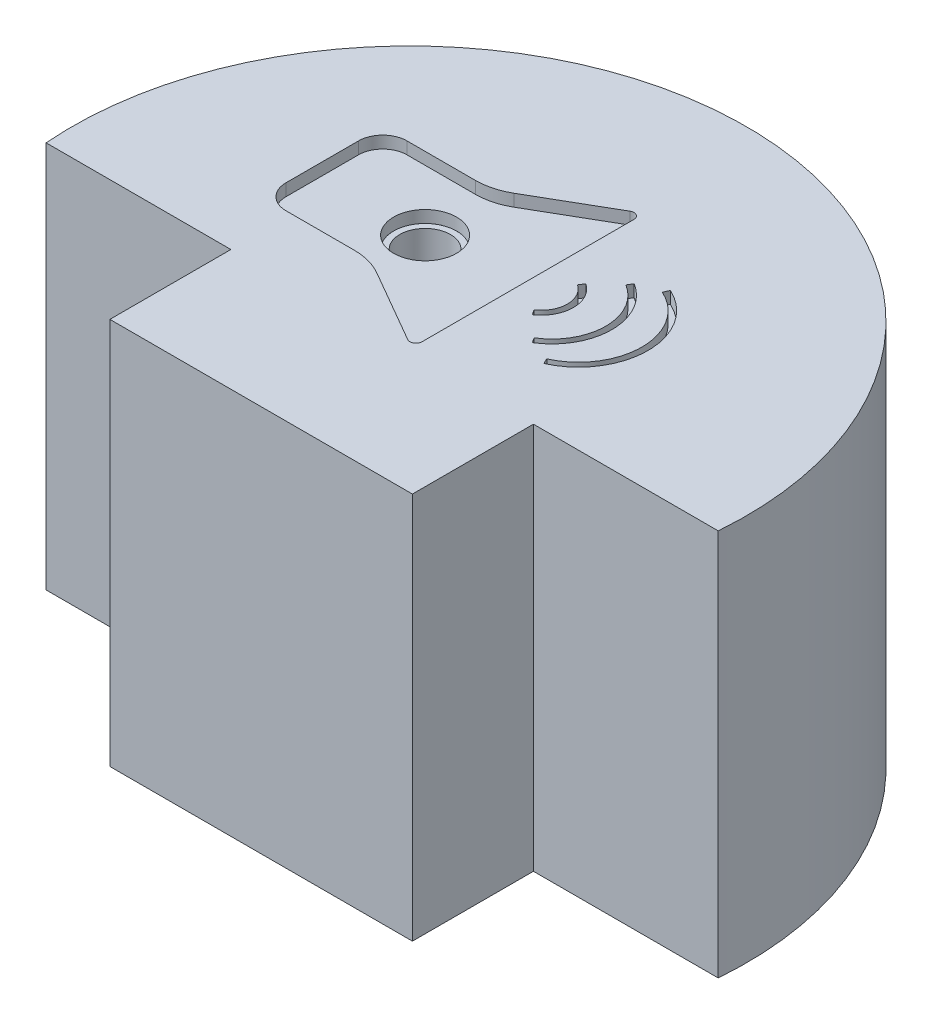
SolidWorks part; units mm, degrees
ref_plane "Alzado" through (0, 0, 0) normal (0, 0, 1) x (1, 0, 0)
ref_plane "Planta" through (0, 0, 0) normal (0, 1, 0) x (1, 0, 0)
ref_plane "Vista lateral" through (0, 0, 0) normal (1, 0, 0) x (0, 0, -1)
sketch "Croquis1" plane through (0, 0, 0) normal (0, 1, 0) x (1, 0, 0)
  line L0 (0, 0) -> (0, 40.0976) construction
  line L1 (-12.5, 0) -> (12.5, 0)
  line L2 (-12.5, 0) -> (-12.5, 10)
  line L3 (12.5, 0) -> (12.5, 10)
  line L4 (-12.5, 10) -> (-27.77, 10)
  line L5 (12.5, 10) -> (27.77, 10)
  arc A0 (-27.77, 10) -> (27.77, 10) centre (0, 12.2376) cw
  point P10 (0, 40.0976)
  dimension "D4" = 27.86
  dimension "D1" = 25
  dimension "D2" = 10
  dimension "D3" = 15.27
extrude "Extruir-Lámina1" add sketch "Croquis1" along normal blind 30 thin thin type one direction reverse wall 2
sketch "Croquis2" plane through (0, 30, 0) normal (0, 1, 0) x (1, 0, 0)
  line L0 (12.5, 10) -> (27.77, 10) construction
  line L1 (12.5, 0) -> (12.5, 10) construction
  line L2 (-12.5, 0) -> (12.5, 0) construction
  line L3 (-12.5, 10) -> (-12.5, 0) construction
  line L4 (-27.77, 10) -> (-12.5, 10) construction
  line L5 (12.5, 10) -> (27.77, 10)
  line L6 (12.5, 0) -> (12.5, 10)
  line L7 (-12.5, 0) -> (12.5, 0)
  line L8 (-12.5, 10) -> (-12.5, 0)
  line L9 (-27.77, 10) -> (-12.5, 10)
  arc A0 (27.77, 10) -> (-27.77, 10) centre (0, 12.2376) ccw construction
  arc A1 (27.77, 10) -> (-27.77, 10) centre (0, 12.2376) ccw
extrude "Saliente-Extruir1" add sketch "Croquis2" along normal blind 2
sketch "Croquis3" plane through (0, 32, 0) normal (0, 1, 0) x (1, 0, 0)
  line L0 (0, 0) -> (0, 40.0976) construction
  line L1 (-14.7383, 20.0488) -> (14.7383, 20.0488) construction
  line L2 (-15, 23.0488) -> (-15, 17.0488)
  line L3 (-13, 25.0488) -> (-7.3397, 25.0488)
  line L4 (-4.8397, 25.7187) -> (1.25, 29.2346)
  line L5 (-4.8397, 14.3789) -> (1.25, 10.863)
  line L6 (-13, 15.0488) -> (-7.3397, 15.0488)
  line L7 (2, 28.8016) -> (2, 11.296)
  arc A0 (27.77, 10) -> (-27.77, 10) centre (0, 12.2376) ccw construction
  arc A1 (-15, 17.0488) -> (-13, 15.0488) centre (-13, 17.0488) ccw
  arc A2 (-15, 23.0488) -> (-13, 25.0488) centre (-13, 23.0488) cw
  arc A3 (-4.8397, 14.3789) -> (-7.3397, 15.0488) centre (-7.3397, 10.0488) ccw
  arc A4 (-7.3397, 25.0488) -> (-4.8397, 25.7187) centre (-7.3397, 30.0488) ccw
  arc A5 (1.25, 10.863) -> (2, 11.296) centre (1.5, 11.296) ccw
  arc A6 (1.25, 29.2346) -> (2, 28.8016) centre (1.5, 28.8016) cw
  point P8 (0, 20.0488)
  point P17 (-15, 15.0488)
  point P20 (-15, 25.0488)
  point P23 (-6, 15.0488)
  point P26 (-6, 25.0488)
  point P29 (2, 10.43)
  point P32 (2, 29.6676)
  dimension "D2" = 2
  dimension "D7" = 5
  dimension "D8" = 0.5
  dimension "D1" = 5
  dimension "D3" = 9
  dimension "D4" = 210
  dimension "D5" = 8
  dimension "D6" = 15
extrude "Cortar-Extruir1" cut sketch "Croquis3" against normal blind 1
sketch "Croquis4" plane through (0, 32, 0) normal (0, 1, 0) x (1, 0, 0)
  line L0 (4, 19.9985) -> (8.73, 19.9985) construction
  line L1 (4.4826, 21.9985) -> (4.4826, 17.9985) construction
  line L2 (6.4826, 23.9985) -> (6.4826, 15.9985) construction
  line L3 (8.73, 19.9985) -> (11.7176, 19.9985) construction
  line L4 (8.4826, 24.9985) -> (8.4826, 14.9985) construction
  line L5 (2, 11.296) -> (2, 28.8016) construction
  arc A0 (4.4826, 21.9985) -> (4.4826, 17.9985) centre (3.1584, 19.9985) cw
  arc A1 (6.4826, 23.9985) -> (6.4826, 15.9985) centre (4.0465, 19.9985) cw
  arc A2 (8.4826, 24.9985) -> (8.4826, 14.9985) centre (6.2362, 19.9985) cw
  point P11 (2, 20.0488)
  dimension "D7" = 4.6834
  dimension "D1" = 4
  dimension "D2" = 8
  dimension "D3" = 10
  dimension "D6" = 2
extrude "Cortar-Extruir-Lámina2" cut sketch "Croquis4" against normal blind 1 thin thin type mid plane wall 0.5
sketch "Croquis5" plane through (0, 0, -2) normal (0, 0, -1) x (-1, 0, 0)
  line L0 (0, 0) -> (0, 5.1) construction
  line L1 (-10, 5.1) -> (10, 5.1)
  dimension "D1" = 20
  dimension "D2" = 5.1
extrude "Extruir-Lámina2" add sketch "Croquis5" along normal blind 1 thin thin type mid plane wall 0.5
sketch "Croquis6" plane through (0, 0, -12) normal (0, 0, -1) x (-1, 0, 0)
  line L0 (-18.5, 0) -> (-18.5, 5.1) construction
  line L1 (-27.86, 0) -> (27.86, 0) construction
  line L2 (-23.5, 5.1) -> (-13.5, 5.1)
  line L4 (0, 0) -> (0, 9.3836) construction
  line L5 (23.5, 5.1) -> (13.5, 5.1)
  line L6 (-10.5, 30) -> (-10.5, 0) construction
  dimension "D1" = 5.1
  dimension "D2" = 10
  dimension "D3" = 3
extrude "Extruir-Lámina3" add sketch "Croquis6" along normal blind 1 thin thin type mid plane wall 0.5
sketch "Croquis7" plane through (0, 32, 0) normal (0, 1, 0) x (1, 0, 0)
  line L0 (-15, 20.0488) -> (2, 20.0488) construction
  line L1 (-15, 23.0488) -> (-15, 17.0488) construction
  line L2 (2, 11.296) -> (2, 28.8016) construction
  circle A0 centre (-6.5, 20.0488) radius 2.6
  dimension "D1" = 5.2
extrude "Cortar-Extruir2" cut sketch "Croquis7" against normal blind 11
sketch "Croquis8" plane through (0, 30, 0) normal (0, -1, 0) x (1, 0, 0)
  circle A4 centre (-6.5, -20.0488) radius 2.6 construction
  circle A5 centre (-6.5, -20.0488) radius 2.1
  circle A6 centre (-6.5, -20.0488) radius 2.1
  circle A7 centre (-6.5, -20.0488) radius 2.6
  dimension "D1" = 0.5
extrude "Saliente-Extruir2" add sketch "Croquis8" along normal blind 3 separate body
